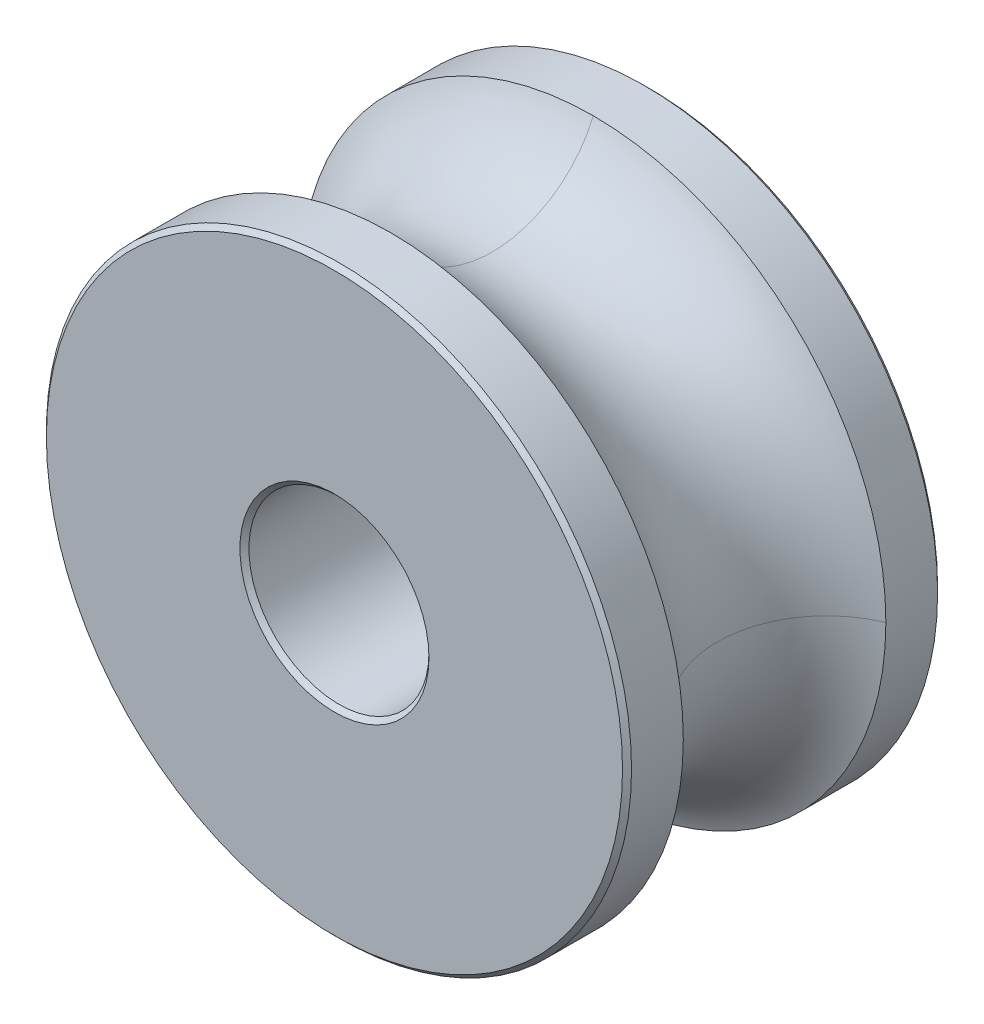
SolidWorks part; units mm, degrees
ref_plane "前视基准面" through (0, 0, 0) normal (0, 0, 1) x (1, 0, 0)
ref_plane "上视基准面" through (0, 0, 0) normal (0, 1, 0) x (1, 0, 0)
ref_plane "右视基准面" through (0, 0, 0) normal (1, 0, 0) x (0, 0, -1)
sketch "草图1" plane through (0, 0, 0) normal (0, 0, 1) x (1, 0, 0)
  circle A0 centre (0, 0) radius 2
  circle A1 centre (0, 0) radius 6.5
  dimension "D1" = 4
  dimension "D2" = 13
extrude "凸台-拉伸1" add sketch "草图1" along normal mid plane 7
sketch "草图2" plane through (0, 0, 0) normal (1, 0, 0) x (0, 0, -1)
  line L3 (-2.25, 6.5) -> (2.25, 6.5)
  line L4 (3.5, 6.5) -> (-3.5, 6.5) construction
  arc A0 (-2.25, 6.5) -> (2.25, 6.5) centre (0, 7.4375) ccw
  point P9 (0, 5)
  dimension "D1" = 4.5
  dimension "D2" = 1.5
sweep "切除-扫描1" cut profiles "草图2" path edge at (6.5, 0, -3.5)
chamfer "倒角1" distance 0.1 angle 45 4 edges at (6.5, 0, -3.5) (6.5, 0, 3.5) (2, 0, 3.5) (2, 0, -3.5)
